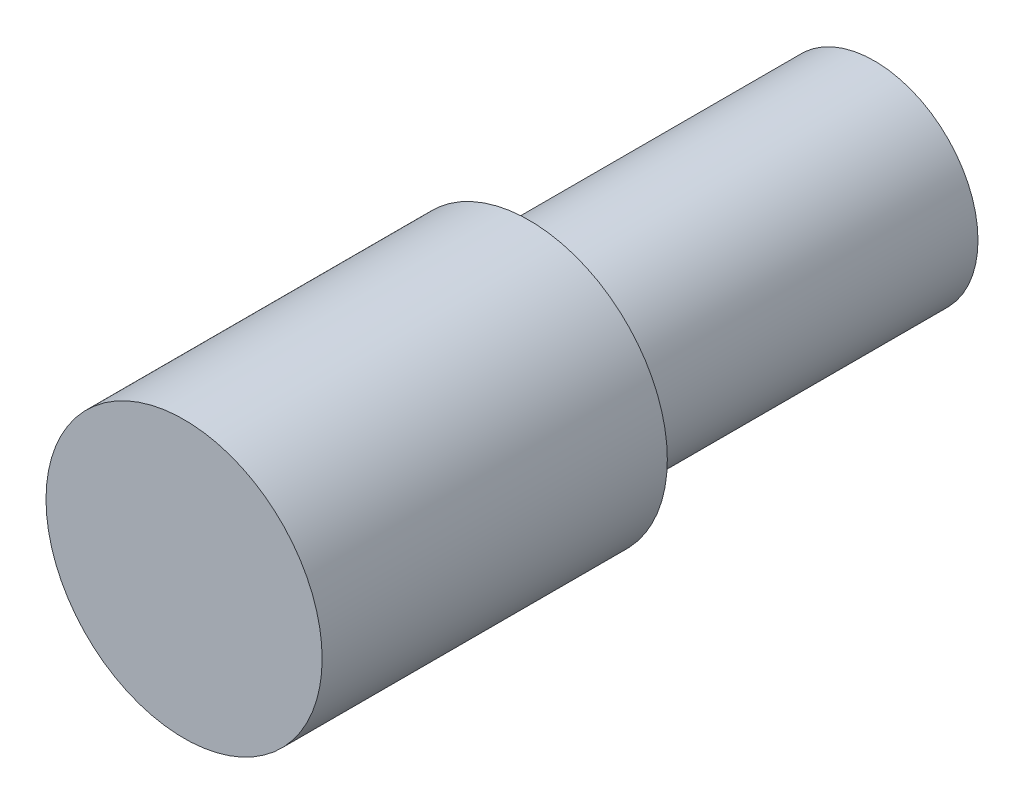
SolidWorks part; units mm, degrees
ref_plane "Front Plane" through (0, 0, 0) normal (0, 0, 1) x (1, 0, 0)
ref_plane "Top Plane" through (0, 0, 0) normal (0, 1, 0) x (1, 0, 0)
ref_plane "Right Plane" through (0, 0, 0) normal (1, 0, 0) x (0, 0, -1)
sketch "Sketch1" plane through (0, 0, 0) normal (0, 0, 1) x (1, 0, 0)
  circle A0 centre (0, 0) radius 1.5
  dimension "D1" = 3
extrude "Boss-Extrude1" add sketch "Sketch1" along normal blind 5
sketch "Sketch2" plane through (0, 0, 5) normal (0, 0, 1) x (1, 0, 0)
  circle A0 centre (0, 0) radius 2
  dimension "D1" = 4
extrude "Boss-Extrude2" add sketch "Sketch2" along normal blind 5
